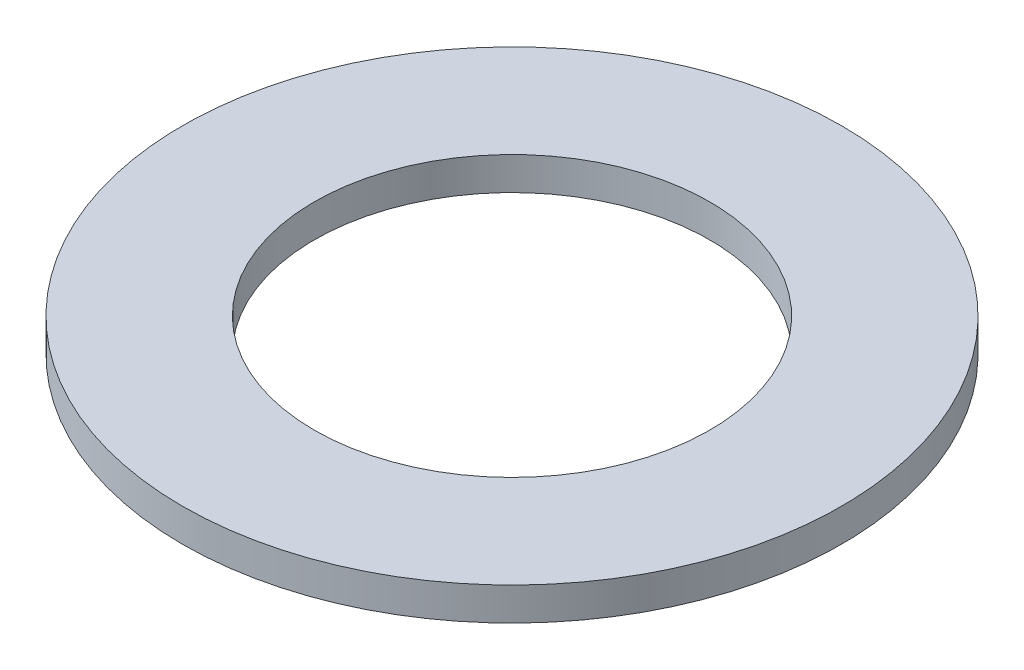
SolidWorks part; units mm, degrees
ref_plane "Front Plane" through (0, 0, 0) normal (0, 0, 1) x (1, 0, 0)
ref_plane "Top Plane" through (0, 0, 0) normal (0, 1, 0) x (1, 0, 0)
ref_plane "Right Plane" through (0, 0, 0) normal (1, 0, 0) x (0, 0, -1)
sketch "Sketch1" plane through (0, 0, 0) normal (0, 1, 0) x (1, 0, 0)
  circle A0 centre (0, 0) radius 10
  circle A1 centre (0, 0) radius 6.0005
  dimension "D1" = 20
  dimension "D2" = 12.001
extrude "Boss-Extrude1" add sketch "Sketch1" along normal blind 1
